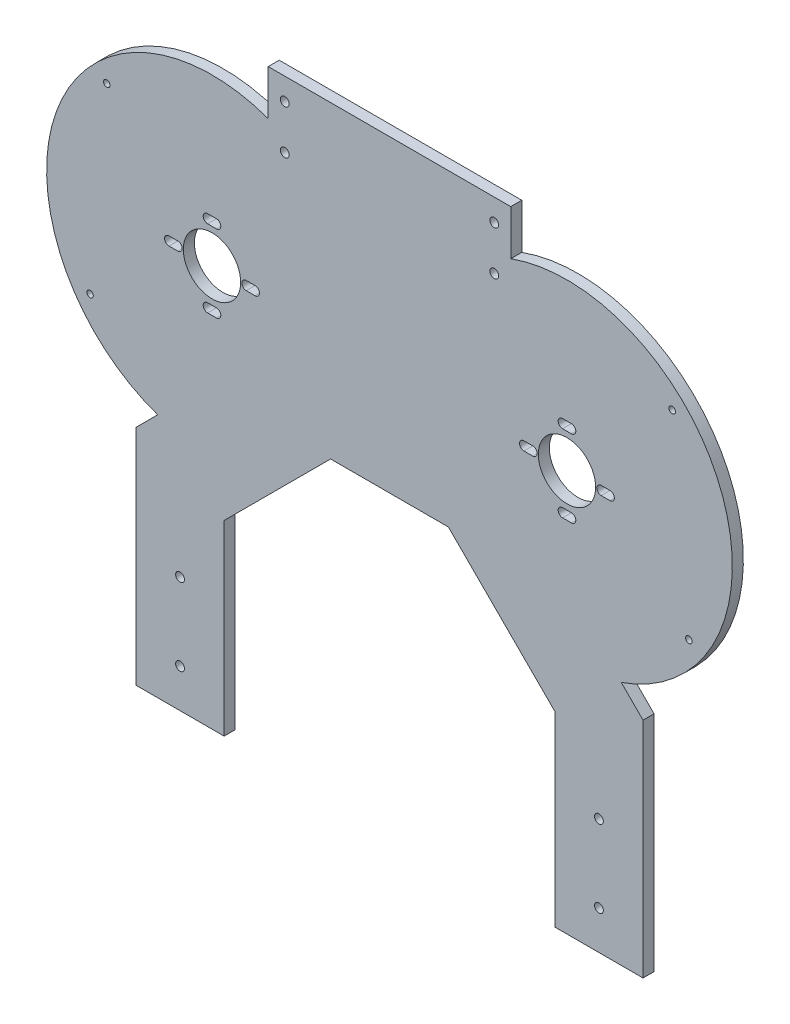
SolidWorks part; units mm, degrees
ref_plane "Front Plane" through (0, 0, 0) normal (0, 0, 1) x (1, 0, 0)
ref_plane "Top Plane" through (0, 0, 0) normal (0, 1, 0) x (1, 0, 0)
ref_plane "Right Plane" through (0, 0, 0) normal (1, 0, 0) x (0, 0, -1)
sketch "Sketch1" plane through (0, 0, 0) normal (0, 0, 1) x (1, 0, 0)
  line L1 (-100, -75) -> (100, -75)
  line L2 (-100, -75) -> (-100, 75)
  line L3 (-100, 75) -> (100, 75)
  line L4 (100, -75) -> (100, 75)
  line L5 (-100, -75) -> (100, 75) construction
  line L6 (-100, 75) -> (100, -75) construction
  line L8 (-47.5, 40) -> (47.5, 40) construction
  line L9 (0, 75) -> (0, -75) construction
  line L10 (-27, -44) -> (27, -44) construction
  line L11 (-27, -44) -> (-27, 28) construction
  line L12 (-27, 28) -> (27, 28) construction
  line L13 (27, -44) -> (27, 28) construction
  line L14 (-27, -44) -> (27, 28) construction
  line L15 (-27, 28) -> (27, -44) construction
  line L23 (-55, 70) -> (55, 70)
  line L24 (-55, 70) -> (-55, -70)
  line L25 (-55, -70) -> (55, -70)
  line L26 (55, 70) -> (55, -70)
  line L27 (-55, 70) -> (55, -70) construction
  line L28 (-55, -70) -> (55, 70) construction
  line L29 (-32.5, 70) -> (32.5, 70) construction
  line L30 (-32.5, 70) -> (-32.5, 55) construction
  line L31 (-32.5, 55) -> (32.5, 55) construction
  line L32 (32.5, 70) -> (32.5, 55) construction
  line L33 (-32.5, 70) -> (32.5, 55) construction
  line L34 (-32.5, 55) -> (32.5, 70) construction
  circle A2 centre (-47.5, 40) radius 2
  circle A3 centre (47.5, 40) radius 2
  circle A4 centre (-27, 28) radius 2 construction
  circle A5 centre (27, 28) radius 2 construction
  circle A6 centre (27, -44) radius 2 construction
  circle A7 centre (-27, -44) radius 2 construction
  circle A8 centre (-47.5, 60) radius 2
  circle A10 centre (47.5, 60) radius 2
  point P0 (0, 0)
  point P15 (0, 40)
  point P18 (0, -8)
  point P56 (0, 0)
  point P63 (0, 62.5)
  dimension "D3" = 4
  dimension "D4" = 20
  dimension "D5" = 4
  dimension "D8" = 4
  dimension "D1" = 150
  dimension "D2" = 200
  dimension "D6" = 72
  dimension "D7" = 54
  dimension "D14" = 30
  dimension "D15" = 140
  dimension "D16" = 110
  dimension "D17" = 95
  dimension "D18" = 12
  dimension "D19" = 15
  dimension "D20" = 65
extrude "Boss-Extrude1" add sketch "Sketch1" along normal blind 5 contours L23 L32 L31 L30 L24 L25 L26 A7 A6 A5 A4 A3 A2 | L2 L1 L4 L3
sketch "Sketch2" plane through (0, 0, 0) normal (0, 0, 1) x (1, 0, 0)
  line L0 (-55, -70) -> (-100.8579, -115.8579) construction
  line L1 (-55, 70) -> (-55, -70) construction
  line L2 (-55, -41.7157) -> (-115, -101.7157)
  line L3 (-26.7157, -70) -> (-86.7157, -130)
  line L4 (-55, -70) -> (55, -70) construction
  line L5 (-115, -101.7157) -> (-86.7157, -130)
  line L6 (-115, -101.7157) -> (-115, -203)
  line L7 (-75, -118.2843) -> (-75, -203)
  line L8 (-75, -203) -> (-115, -203)
  line L9 (0, 75) -> (0, -75) construction
  line L10 (-55, -41.7157) -> (-26.7157, -70)
  line L11 (-55, 70) -> (-55, -70) construction
  line L12 (-115, -203) -> (-75, -203) construction
  circle A0 centre (-95, -150.5) radius 2
  circle A1 centre (-95, -185.5) radius 2
  circle A2 centre (-95, -150.5) radius 2 construction
  circle A4 centre (-95, -185.5) radius 2 construction
  dimension "D1" = 135
  dimension "D2" = 40
  dimension "D3" = 40
  dimension "D4" = 75
  dimension "D5" = 0
extrude "Boss-Extrude2" add sketch "Sketch2" along normal blind 5
mirror "Mirror1" about plane through (0, 0, 0) normal (1, 0, 0) of "Boss-Extrude2"
sketch "Sketch3" plane through (0, 0, 5) normal (0, 0, 1) x (1, 0, 0)
  line L0 (0, 31.3301) -> (0, 52.1198) construction
  line L1 (-80.5, -21) -> (-128.2297, 26.7297) construction
  line L2 (-80.5, -21) -> (80.5, -21) construction
  line L3 (-80.5, -21) -> (-148, -21) construction
  line L4 (-80.5, -21) -> (-135.7928, -59.7164) construction
  line L5 (-82.5, -3.5) -> (-78.5, -3.5) construction
  line L6 (-82.5, -1.5) -> (-78.5, -1.5)
  line L7 (-82.5, -5.5) -> (-78.5, -5.5)
  line L8 (-82.5, -38.5) -> (-78.5, -38.5) construction
  line L9 (-82.5, -40.5) -> (-78.5, -40.5)
  line L10 (-82.5, -36.5) -> (-78.5, -36.5)
  line L11 (-96, -21) -> (-100, -21) construction
  line L12 (-96, -23) -> (-100, -23)
  line L13 (-96, -19) -> (-100, -19)
  line L14 (-80.5, -21) -> (-80.5, -13.7655) construction
  line L15 (-65, -21) -> (-61, -21) construction
  line L16 (-65, -23) -> (-61, -23)
  line L17 (-65, -19) -> (-61, -19)
  line L18 (82.5, -3.5) -> (78.5, -3.5) construction
  line L19 (82.5, -1.5) -> (78.5, -1.5)
  line L20 (82.5, -5.5) -> (78.5, -5.5)
  line L21 (65, -21) -> (61, -21) construction
  line L22 (65, -23) -> (61, -23)
  line L23 (65, -19) -> (61, -19)
  line L24 (96, -21) -> (100, -21) construction
  line L25 (96, -23) -> (100, -23)
  line L26 (96, -19) -> (100, -19)
  line L27 (82.5, -38.5) -> (78.5, -38.5) construction
  line L28 (82.5, -40.5) -> (78.5, -40.5)
  line L29 (82.5, -36.5) -> (78.5, -36.5)
  circle A0 centre (-80.5, -21) radius 75
  circle A1 centre (-80.5, -3.5) radius 2 construction
  circle A2 centre (80.5, -21) radius 75
  circle A3 centre (-80.5, -21) radius 60
  circle A4 centre (80.5, -21) radius 60
  circle A5 centre (-47.5, 40) radius 2 construction
  circle A6 centre (-47.5, 40) radius 2
  circle A7 centre (47.5, 40) radius 2
  circle A8 centre (-63, -21) radius 2 construction
  circle A9 centre (-80.5, -38.5) radius 2 construction
  circle A10 centre (-98, -21) radius 2 construction
  circle A11 centre (98, -21) radius 2 construction
  circle A12 centre (80.5, -38.5) radius 2 construction
  circle A13 centre (63, -21) radius 2 construction
  circle A14 centre (80.5, -3.5) radius 2 construction
  circle A15 centre (-80.5, -21) radius 13
  circle A16 centre (80.5, -21) radius 13
  circle A17 centre (-128.2297, 26.7297) radius 1.4732
  circle A18 centre (-135.7928, -59.7164) radius 1.4732
  circle A19 centre (-80.5, -21) radius 67.5 construction
  circle A20 centre (128.2297, 26.7297) radius 1.4732
  circle A21 centre (135.7928, -59.7164) radius 1.4732
  arc A22 (-82.5, -1.5) -> (-82.5, -5.5) centre (-82.5, -3.5) ccw
  arc A23 (-78.5, -5.5) -> (-78.5, -1.5) centre (-78.5, -3.5) ccw
  arc A24 (-82.5, -40.5) -> (-82.5, -36.5) centre (-82.5, -38.5) cw
  arc A25 (-78.5, -36.5) -> (-78.5, -40.5) centre (-78.5, -38.5) cw
  arc A26 (-96, -23) -> (-96, -19) centre (-96, -21) ccw
  arc A27 (-100, -19) -> (-100, -23) centre (-100, -21) ccw
  arc A28 (-65, -23) -> (-65, -19) centre (-65, -21) cw
  arc A29 (-61, -19) -> (-61, -23) centre (-61, -21) cw
  arc A30 (82.5, -1.5) -> (82.5, -5.5) centre (82.5, -3.5) cw
  arc A31 (78.5, -5.5) -> (78.5, -1.5) centre (78.5, -3.5) cw
  arc A32 (65, -23) -> (65, -19) centre (65, -21) ccw
  arc A33 (61, -19) -> (61, -23) centre (61, -21) ccw
  arc A34 (96, -23) -> (96, -19) centre (96, -21) cw
  arc A35 (100, -19) -> (100, -23) centre (100, -21) cw
  arc A36 (82.5, -40.5) -> (82.5, -36.5) centre (82.5, -38.5) ccw
  arc A37 (78.5, -36.5) -> (78.5, -40.5) centre (78.5, -38.5) ccw
  point P28 (-80.5, -21)
  point P48 (-80.5, -3.5)
  point P53 (-98, -21)
  point P60 (-63, -21)
  point P67 (-80.5, -38.5)
  point P77 (80.5, -3.5)
  point P84 (63, -21)
  point P91 (98, -21)
  point P98 (80.5, -38.5)
  line M3 (115, -101.7157) -> (55, -41.7157)
  line M4 (55, -41.7157) -> (55, 70)
  line M6 (-55, 70) -> (-55, -41.7157)
  line M7 (-55, -41.7157) -> (-115, -101.7157)
  line M11 (-75, -118.2843) -> (-26.7157, -70)
  line M12 (-26.7157, -70) -> (26.7157, -70)
  line M13 (26.7157, -70) -> (75, -118.2843)
  circle M17 centre (-47.5, 40) radius 2
  circle M18 centre (47.5, 40) radius 2
  dimension "D1" = 161
  dimension "D2" = 150
  dimension "D3" = 61
  dimension "D4" = 120
  dimension "D5" = 4
  dimension "D7" = 2
  dimension "D8" = 26
  dimension "D9" = 7.5
  dimension "D10" = 2.9464
  dimension "D15" = 2
  dimension "D6" = 4
  dimension "D11" = 45
  dimension "D12" = 35
  dimension "D13" = 17.5
  dimension "D14" = 4
  dimension "D16" = 4
extrude "Boss-Extrude3" add sketch "Sketch3" against normal up to surface (5 mm away) contours A3 M6 M7 | A3 A0 M6 M7 | A3 A0 M7 M11 M12 M6 M17 | A3 M7 M6 | A4 M3 M4 | A4 M4 M3 | A4 A2 M4 M3 | A4 A2 M3 M4 M12 M13 M18
